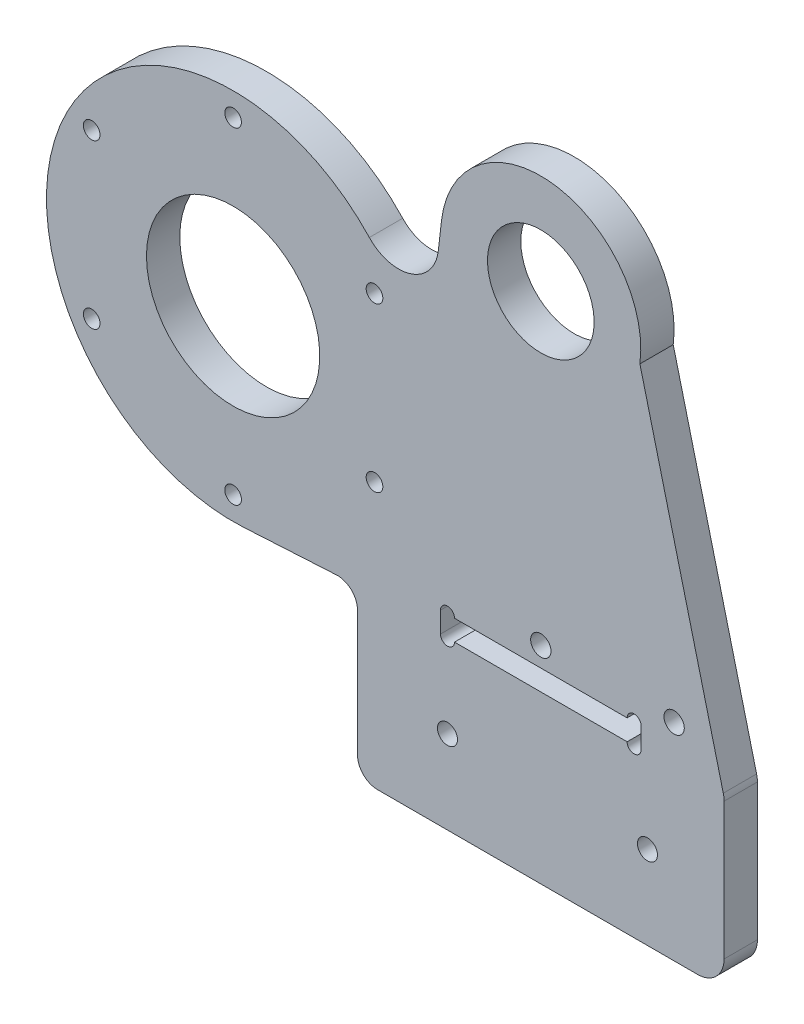
SolidWorks part; units mm, degrees
material "Thornel Mat VMA"
ref_plane "前视基准面" through (0, 0, 0) normal (0, 0, 1) x (1, 0, 0)
ref_plane "上视基准面" through (0, 0, 0) normal (0, 1, 0) x (1, 0, 0)
ref_plane "右视基准面" through (0, 0, 0) normal (1, 0, 0) x (0, 0, -1)
sketch "草图1" plane through (0, 0, 0) normal (0, 0, 1) x (1, 0, 0)
  line L1 (-20, -12.5) -> (20, -12.5)
  line L2 (-20, -12.5) -> (-20, 12.5)
  line L3 (-20, 12.5) -> (20, 12.5)
  line L4 (20, -12.5) -> (20, 12.5)
  line L5 (0, 12.5) -> (0, -12.5) construction
  line L6 (-20, 0) -> (20, 0) construction
  point P0 (0, 0)
  dimension "D1" = 25
  dimension "D2" = 40
extrude "凸台-拉伸1" add sketch "草图1" along normal blind 5
sketch "草图2" plane through (0, 0, 5) normal (0, 0, 1) x (1, 0, 0)
  line L1 (-5, 12.5) -> (-5, 74.5)
  line L2 (-5, 74.5) -> (20, 74.5)
  line L3 (20, 74.5) -> (20, 12.5)
  line L6 (20, 12.5) -> (-20, 12.5) construction
  line L7 (-5, 12.5) -> (20, 12.5)
  dimension "D2" = 25
  dimension "D3" = 62
extrude "凸台-拉伸2" add sketch "草图2" against normal up to surface (5 mm away) up to face at (0, 0, 0)
sketch "草图3" plane through (0, 0, 0) normal (0, 0, -1) x (-1, 0, 0)
  line L0 (-7.5, 74.5) -> (-7.5, 64.5) construction
  line L1 (-20, 74.5) -> (5, 74.5) construction
  circle A0 centre (-7.5, 64.5) radius 8
  dimension "D1" = 16
  dimension "D2" = 10
extrude "切除-拉伸1" cut sketch "草图3" against normal blind 14
sketch "草图4" plane through (0, 0, 0) normal (0, 0, -1) x (-1, 0, 0)
  line L0 (5, 74.5) -> (20, 12.5)
  line L1 (20, 12.5) -> (5, 12.5)
  line L2 (5, 12.5) -> (5, 74.5)
extrude "凸台-拉伸3" add sketch "草图4" against normal up to surface (5 mm away) up to face at (-0.5, 64.5, 5)
sketch "草图5" plane through (0, 0, 0) normal (0, 0, -1) x (-1, 0, 0)
  line L0 (5, 74.5) -> (43.9619, 66.9945)
  line L1 (37.1022, 11.5437) -> (20, 12.5)
  line L2 (5, 74.5) -> (20, 12.5)
  arc A0 (37.1022, 11.5437) -> (43.9619, 66.9945) centre (38.6655, 39.5) ccw
  circle A1 centre (-7.5, 64.5) radius 8 construction
  arc A4 (18.6193, 17.6578) -> (10.3141, 48.168) centre (38.6655, 39.5) ccw construction
  arc A5 (10.3141, 48.168) -> (18.6193, 17.6578) centre (38.6655, 39.5) ccw construction
  dimension "D2" = 56
  dimension "D1" = 52.5
  dimension "D3" = 25
extrude "凸台-拉伸4" add sketch "草图5" against normal up to surface (5 mm away) up to face at (-1, 27.3, 5)
sketch "草图6" plane through (0, 0, 0) normal (0, 0, -1) x (-1, 0, 0)
  circle A0 centre (38.6655, 39.5) radius 24.5 construction
  circle A1 centre (38.6655, 64) radius 1.25
  circle A2 centre (59.8831, 51.75) radius 1.25
  circle A3 centre (59.8831, 27.25) radius 1.25
  circle A4 centre (38.6655, 15) radius 1.25
  circle A5 centre (17.4478, 27.25) radius 1.25
  circle A6 centre (17.4478, 51.75) radius 1.25
  point P21 (38.6655, 39.5)
  dimension "D1" = 49
  dimension "D2" = 2.5
  dimension "D3" = 6
extrude "切除-拉伸2" cut sketch "草图6" against normal blind 10
sketch "草图7" plane through (0, 0, 0) normal (0, 0, -1) x (-1, 0, 0)
  circle A0 centre (38.6655, 39.5) radius 13
  dimension "D1" = 26
extrude "切除-拉伸3" cut sketch "草图7" against normal blind 10
fillet "圆角1" radius 3 4 edges at (-20, -12.5, 2.5) (20, -12.5, 2.5) (-20, 12.5, 2.5) (20, 74.5, 2.5)
fillet "圆角2" [suppressed] radius 3
sketch "草图8" [suppressed] plane through (0, 0, 0) normal (0, 0, -1) x (-1, 0, 0)
  line L0 (-17, -12.5) -> (-36, -12.5)
  line L1 (-36, -12.5) -> (-36, 12.5)
  line L2 (-20, -9.5) -> (-20, 71.5) construction
  line L3 (-19.8967, 72.2803) -> (-17, -12.5)
  line L4 (-36, 12.5) -> (-19.8967, 72.2803)
  arc A0 (-17, 74.5) -> (-20, 71.5) centre (-17, 71.5) ccw construction
  dimension "D1" = 16
  dimension "D2" = 25
extrude "凸台-拉伸5" [suppressed] add sketch "草图8" against normal up to surface (5 mm away)
fillet "圆角3" [suppressed] radius 2
fillet "圆角4" [suppressed] radius 4
sketch "草图9" plane through (0, 0, 0) normal (0, 0, -1) x (-1, 0, 0)
  line L0 (-17, -12.5) -> (-35, -12.5)
  line L1 (-35, -12.5) -> (-35, 12.5)
  line L2 (-35, 12.5) -> (-19.9086, 72.2348)
  line L3 (-20, -9.5) -> (-20, 71.5) construction
  line L4 (-19.9086, 72.2348) -> (-17, -12.5)
  arc A0 (-17, 74.5) -> (-20, 71.5) centre (-17, 71.5) ccw construction
  dimension "D1" = 15
  dimension "D2" = 25
extrude "凸台-拉伸6" add sketch "草图9" against normal up to surface (5 mm away) up to face at (-51.6655, 39.5, 5)
fillet "圆角5" radius 4 2 edges at (35, 12.5, 2.5) (35, -12.5, 2.5)
sketch "草图10" [suppressed] plane through (0, 0, 0) normal (0, 0, -1) x (-1, 0, 0)
  circle A0 centre (-7.5, 64.5) radius 15
  dimension "D1" = 30
sketch "草图11" [suppressed] plane through (0, 0, 0) normal (0, 0, -1) x (-1, 0, 0)
  line L1 (19.9159, 12.8477) -> (5.5551, 72.2055) construction
  line L2 (5.6921, 71.6391) -> (5.5551, 72.2055)
  arc A0 (5.6921, 71.6391) -> (3.9379, 74.2044) centre (-7.5, 64.5) ccw
  arc A1 (5.5551, 72.2055) -> (2.6393, 74.5) centre (2.6393, 71.5) ccw construction
  arc A2 (5.5551, 72.2055) -> (3.9379, 74.2044) centre (2.6393, 71.5) ccw
  dimension "D1" = 30
extrude "切除-拉伸5" [suppressed] cut sketch "草图11" against normal blind 10
sketch "草图12" plane through (0, 0, 0) normal (0, 0, -1) x (-1, 0, 0)
  circle A0 centre (-7.5, 64.5) radius 15
  circle A1 centre (-7.5, 64.5) radius 8 construction
  circle A2 centre (-7.5, 64.5) radius 8
  dimension "D1" = 30
extrude "凸台-拉伸7" add sketch "草图12" against normal up to surface (5 mm away) up to face at (-51.6655, 39.5, 5)
sketch "草图13" plane through (0, 0, 0) normal (0, 0, -1) x (-1, 0, 0)
  line L0 (7.4014, 66.2172) -> (7.8819, 62.0471)
  line L1 (-3.8457, 79.0481) -> (45.4868, 66.6564)
  arc A0 (45.4868, 66.6564) -> (18.223, 58.6339) centre (38.6655, 39.5) ccw
  arc A1 (7.4014, 66.2172) -> (-3.8457, 79.0481) centre (-7.5, 64.5) ccw
  arc A2 (3.6803, 74.5) -> (-22.3667, 62.505) centre (-7.5, 64.5) ccw construction
  arc A3 (7.8819, 62.0471) -> (18.223, 58.6339) centre (13.8425, 62.734) ccw
  dimension "D1" = 56
  dimension "D2" = 6
extrude "切除-拉伸6" cut sketch "草图13" against normal blind 10
sketch "草图14" plane through (0, 0, 5) normal (0, 0, 1) x (1, 0, 0)
  line L0 (-7.55, 12.45) -> (22.55, 12.45)
  line L1 (22.55, 12.45) -> (22.55, 15.55)
  line L2 (22.55, 15.55) -> (-7.55, 15.55)
  line L3 (-7.55, 15.55) -> (-7.55, 12.45)
  line L4 (-7.5, 12.5) -> (22.5, 12.5)
  line L5 (22.5, 12.5) -> (22.5, 15.5)
  line L6 (22.5, 15.5) -> (-7.5, 15.5)
  line L7 (-7.5, 15.5) -> (-7.5, 12.5)
  line L8 (-7.5, 12.5) -> (22.5, 12.5) construction
  line L9 (22.5, 12.5) -> (22.5, 15.5) construction
  line L10 (22.5, 15.5) -> (-7.5, 15.5) construction
  line L11 (-7.5, 15.5) -> (-7.5, 12.5) construction
  dimension "D1" = 0
  dimension "D2" = 0.05
extrude "切除-拉伸7" cut sketch "草图14" against normal up to surface (5 mm away) up to face at (-1.9751, 22.336, 0)
sketch "草图15" plane through (0, 0, 5) normal (0, 0, 1) x (1, 0, 0)
  line L0 (22.55, 15.55) -> (-7.55, 15.55) construction
  line L1 (-7.55, 12.45) -> (22.55, 12.45) construction
  circle A0 centre (-6.5, 15.55) radius 1.05
  circle A1 centre (21.5, 15.55) radius 1.05
  circle A2 centre (-6.5, 12.45) radius 1.05
  circle A3 centre (21.5, 12.45) radius 1.05
  dimension "D1" = 2.1
extrude "切除-拉伸8" cut sketch "草图15" against normal up to surface (5 mm away) up to face at (7.5, 14, 0)
sketch "草图16" [suppressed] plane through (0, 0, 0) normal (0, 0, -1) x (-1, 0, 0)
  line L0 (6.55, 15.55) -> (-23.55, 15.55)
  line L1 (-23.55, 15.55) -> (-23.55, 12.45)
  line L2 (-23.55, 12.45) -> (6.55, 12.45)
  line L3 (6.55, 12.45) -> (6.55, 15.55)
  line L4 (6.5, 15.5) -> (-23.5, 15.5)
  line L5 (-23.5, 15.5) -> (-23.5, 12.5)
  line L6 (-23.5, 12.5) -> (6.5, 12.5)
  line L7 (6.5, 12.5) -> (6.5, 15.5)
  line L8 (6.5, 15.5) -> (-23.5, 15.5) construction
  line L9 (-23.5, 15.5) -> (-23.5, 12.5) construction
  line L10 (-23.5, 12.5) -> (6.5, 12.5) construction
  line L11 (6.5, 12.5) -> (6.5, 15.5) construction
  dimension "D1" = 0
  dimension "D2" = 0.05
extrude "切除-拉伸9" [suppressed] cut sketch "草图16" against normal up to surface (5 mm away)
sketch "草图17" [suppressed] plane through (0, 0, 0) normal (0, 0, -1) x (-1, 0, 0)
  line L0 (6.55, 15.55) -> (-23.55, 15.55) construction
  line L1 (-23.55, 12.45) -> (6.55, 12.45) construction
  circle A0 centre (-22.5, 15.55) radius 1.05
  circle A1 centre (-22.5, 12.45) radius 1.05
  circle A2 centre (5.5, 15.55) radius 1.05
  circle A3 centre (5.5, 12.45) radius 1.05
  dimension "D1" = 2.1
extrude "切除-拉伸10" [suppressed] cut sketch "草图17" against normal up to surface (5 mm away)
sketch "草图18" plane through (0, 0, 0) normal (0, 0, -1) x (-1, 0, 0)
  circle A0 centre (-23.5, 0) radius 1.5 construction
  circle A1 centre (6.5, 0) radius 1.5 construction
  circle A2 centre (-23.5, 0) radius 1.5
  circle A3 centre (6.5, 0) radius 1.5
extrude "切除-拉伸12" cut sketch "草图18" against normal blind 10
sketch "草图19" [suppressed] plane through (0, 0, 0) normal (0, 0, -1) x (-1, 0, 0)
  circle A0 centre (-8.5, 18.5) radius 1.25 construction
  circle A1 centre (-28.5, 18.5) radius 1.25 construction
  circle A2 centre (-8.5, 18.5) radius 1.25 construction
  circle A3 centre (-28.5, 18.5) radius 1.25 construction
  circle A4 centre (-28.5, 18.5) radius 1.525
  circle A5 centre (-8.5, 18.5) radius 1.525
  dimension "D1" = 3.05
extrude "切除-拉伸13" [suppressed] cut sketch "草图19" against normal blind 10
sketch "草图20" plane through (0, 0, 0) normal (0, 0, -1) x (-1, 0, 0)
  circle A0 centre (-27.5, 18.5) radius 1.25 construction
  circle A1 centre (-7.5, 18.5) radius 1.25 construction
  circle A2 centre (-27.5, 18.5) radius 1.25 construction
  circle A3 centre (-7.5, 18.5) radius 1.25 construction
  circle A4 centre (-27.5, 18.5) radius 1.525
  circle A5 centre (-7.5, 18.5) radius 1.525
  dimension "D1" = 3.05
extrude "切除-拉伸14" cut sketch "草图20" against normal blind 10
